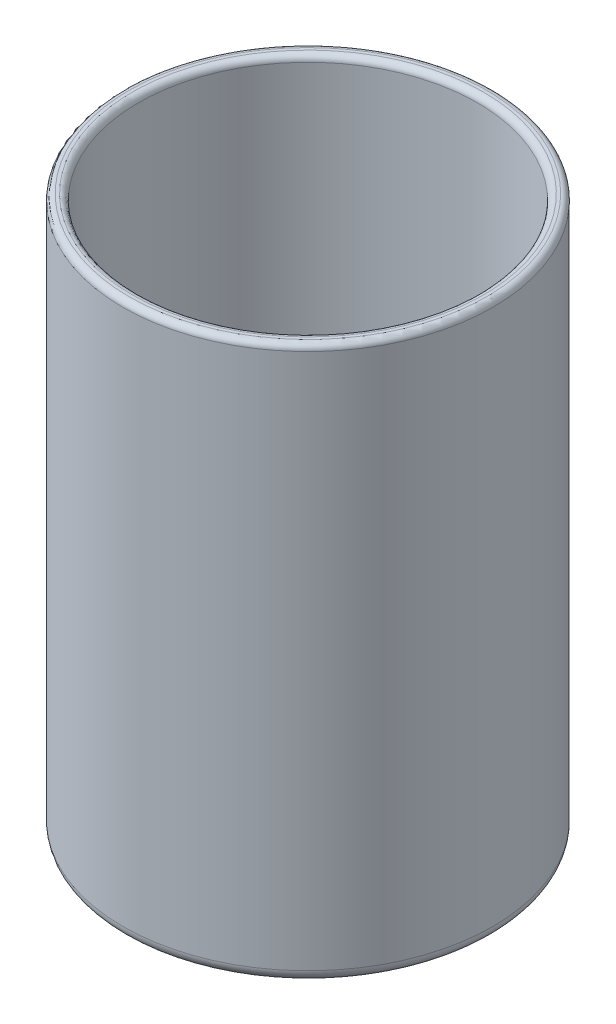
SolidWorks part; units mm, degrees
ref_plane "Front Plane" through (0, 0, 0) normal (0, 0, 1) x (1, 0, 0)
ref_plane "Top Plane" through (0, 0, 0) normal (0, 1, 0) x (1, 0, 0)
ref_plane "Right Plane" through (0, 0, 0) normal (1, 0, 0) x (0, 0, -1)
sketch "Sketch1" plane through (0, 0, 0) normal (0, 1, 0) x (1, 0, 0)
  circle A1 centre (0, 0) radius 38.1
  dimension "D2" = 76.2
extrude "Boss-Extrude1" add sketch "Sketch1" along normal blind 5.08 contours A1
sketch "Sketch3" plane through (0, 5.08, 0) normal (0, 1, 0) x (1, 0, 0)
  circle A0 centre (0, 0) radius 34.925
  circle A1 centre (0, 0) radius 38.1
  dimension "D1" = 69.85
  dimension "D2" = 76.2
extrude "Boss-Extrude2" add sketch "Sketch3" along normal blind 109.22
fillet "Fillet1" radius 1.27 2 edges at (0, 114.3, 34.925) (0, 114.3, 38.1)
fillet "Fillet2" radius 2.54 1 edges at (0, 0, 38.1)
